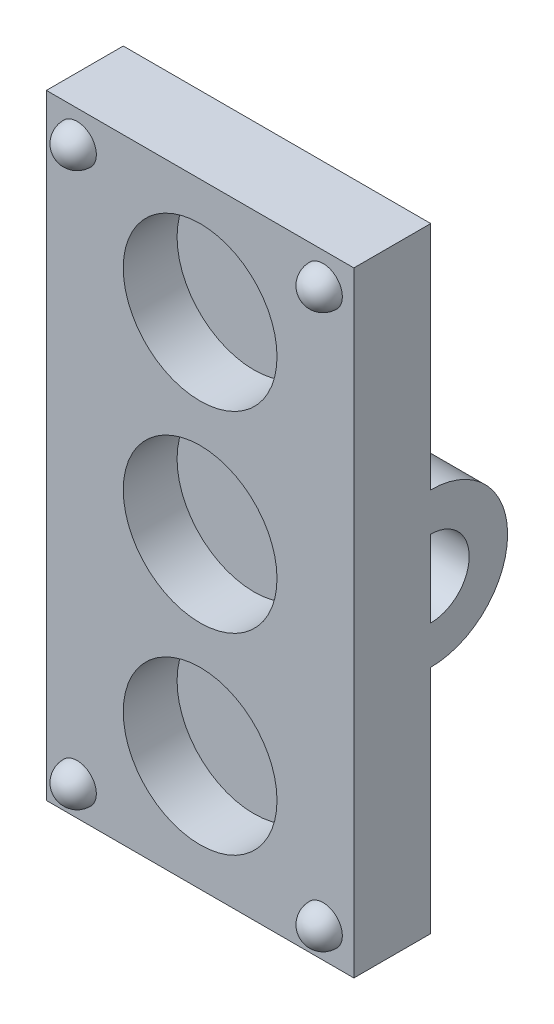
SolidWorks part; units mm, degrees
ref_plane "Front Plane" through (0, 0, 0) normal (0, 0, 1) x (1, 0, 0)
ref_plane "Top Plane" through (0, 0, 0) normal (0, 1, 0) x (1, 0, 0)
ref_plane "Right Plane" through (0, 0, 0) normal (1, 0, 0) x (0, 0, -1)
sketch "Sketch3" plane through (0, 0, 0) normal (0, 0, 1) x (1, 0, 0)
  line L1 (-20, 40) -> (20, 40)
  line L2 (-20, 40) -> (-20, -40)
  line L3 (-20, -40) -> (20, -40)
  line L4 (20, 40) -> (20, -40)
  line L5 (-20, 40) -> (20, -40) construction
  line L6 (-20, -40) -> (20, 40) construction
  point P0 (0, 0)
  dimension "D1" = 80
  dimension "D2" = 40
extrude "Boss-Extrude1" add sketch "Sketch3" along normal blind 10
sketch "Sketch4" plane through (0, 0, 10) normal (0, 0, 1) x (1, 0, 0)
  line L0 (20, 40) -> (-20, 40) construction
  line L1 (-20, -40) -> (20, -40) construction
  line L2 (20, -40) -> (20, 40) construction
  circle A0 centre (0, 25) radius 10
  circle A1 centre (0, 0) radius 10
  circle A2 centre (0, -25) radius 10
  dimension "D5" = 20
  dimension "D6" = 20
  dimension "D7" = 20
  dimension "D1" = 15
  dimension "D2" = 15
  dimension "D3" = 20
  dimension "D4" = 20
extrude "Cut-Extrude4" cut sketch "Sketch4" against normal blind 7
sketch "Sketch5" plane through (0, 0, 10) normal (0, 0, 1) x (1, 0, 0)
  line L0 (20, -40) -> (20, 40) construction
  line L2 (20, 40) -> (-20, 40) construction
  line L4 (16, 38.5) -> (16, 33.5)
  arc A1 (16, 38.5) -> (16, 33.5) centre (16, 36) ccw
  dimension "D6" = 5
  dimension "D1" = 4
  dimension "D2" = 4
revolve "Revolve1" add sketch "Sketch5" angle 360 about L4
sketch "Sketch7" plane through (0, 0, 10) normal (0, 0, 1) x (1, 0, 0)
  line L0 (-20, 40) -> (-20, -40) construction
  line L3 (20, 40) -> (-20, 40) construction
  line L4 (-20, -40) -> (20, -40) construction
  line L8 (-16, -33.5) -> (-16, -38.5)
  line L10 (-16, 38.5) -> (-16, 33.5)
  arc A0 (-16, 38.5) -> (-16, 33.5) centre (-16, 36) ccw
  arc A1 (-16, -33.5) -> (-16, -38.5) centre (-16, -36) ccw
  dimension "D3" = 5
  dimension "D4" = 5
  dimension "D1" = 4
  dimension "D2" = 4
  dimension "D6" = 4
  dimension "D7" = 4
revolve "Revolve2" add sketch "Sketch7" angle 360 about L8
sketch "Sketch8" plane through (0, 0, 10) normal (0, 0, 1) x (1, 0, 0)
  line L0 (20, -40) -> (20, 40) construction
  line L1 (-20, -40) -> (20, -40) construction
  line L2 (16, -33.5) -> (16, -38.5)
  arc A0 (16, -33.5) -> (16, -38.5) centre (16, -36) ccw
  dimension "D3" = 5
  dimension "D1" = 4
  dimension "D2" = 4
revolve "Revolve3" add sketch "Sketch8" angle 360 about L2
sketch "Sketch12" plane through (-20, 0, 0) normal (-1, 0, 0) x (0, 0, 1)
  line L0 (0, 10) -> (0, -10)
  arc A0 (0, 10) -> (0, -10) centre (0, 0) ccw
  dimension "D1" = 20
extrude "Boss-Extrude3" add sketch "Sketch12" against normal blind 40
sketch "Sketch13" plane through (-20, 0, 0) normal (-1, 0, 0) x (0, 0, 1)
  line L0 (0, 5) -> (0, -5)
  arc A0 (0, 5) -> (0, -5) centre (0, 0) ccw
  dimension "D1" = 10
extrude "Cut-Extrude5" cut sketch "Sketch13" against normal blind 40
